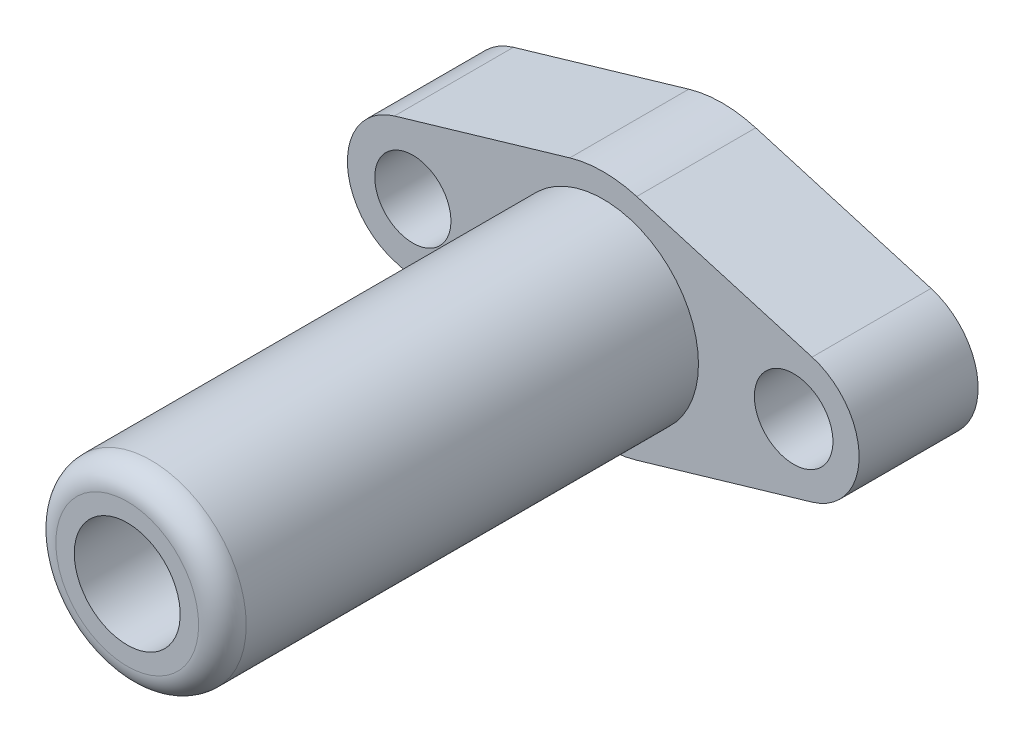
SolidWorks part; units mm, degrees
ref_plane "前视基准面" through (0, 0, 0) normal (0, 0, 1) x (1, 0, 0)
ref_plane "上视基准面" through (0, 0, 0) normal (0, 1, 0) x (1, 0, 0)
ref_plane "右视基准面" through (0, 0, 0) normal (1, 0, 0) x (0, 0, -1)
other "Configuration Table"
sketch "草图1" plane through (0, 0, 0) normal (0, 0, 1) x (1, 0, 0)
  circle A0 centre (0, 0) radius 4
  dimension "D1" = 8
extrude "凸台-拉伸1" add sketch "草图1" along normal blind 20
sketch "草图2" plane through (0, 0, 0) normal (0, 0, -1) x (-1, 0, 0)
  line L0 (-6.3901, 0) -> (7.5604, 0) construction
  line L1 (-8.7734, 2.639) -> (-1.4063, 4.7982)
  line L2 (-8.7734, -2.639) -> (-1.4063, -4.7982)
  line L3 (0, 55) -> (0, -55) construction
  line L4 (8.7734, -2.639) -> (1.4063, -4.7982)
  line L5 (8.7734, 2.639) -> (1.4063, 4.7982)
  circle A0 centre (-8, 0) radius 1.65
  circle A1 centre (8, 0) radius 1.6
  arc A2 (-1.4063, -4.7982) -> (1.4063, -4.7982) centre (0, 0) ccw
  arc A3 (-8.7734, 2.639) -> (-8.7734, -2.639) centre (-8, 0) ccw
  arc A4 (8.7734, -2.639) -> (8.7734, 2.639) centre (8, 0) ccw
  arc A5 (1.4063, 4.7982) -> (-1.4063, 4.7982) centre (0, 0) ccw
  dimension "D1" = 3.3
  dimension "D3" = 3.2
  dimension "D5" = 10
  dimension "D6" = 5.5
  dimension "D7" = 5.5
  dimension "D2" = 8
  dimension "D4" = 16
extrude "凸台-拉伸2" add sketch "草图2" along normal blind 5
sketch "草图3" plane through (0, 0, -5) normal (0, 0, -1) x (-1, 0, 0)
  circle A0 centre (0, 0) radius 2.25
  dimension "D1" = 4.5
extrude "切除-拉伸1" cut sketch "草图3" against normal blind 12
sketch "草图4" plane through (0, 0, 7) normal (0, 0, -1) x (-1, 0, 0)
  circle A0 centre (0, 0) radius 2.225
  dimension "D1" = 4.45
extrude "切除-拉伸2" cut sketch "草图4" against normal through all
fillet "圆角2" radius 1 1 edges at (4, 0, 20)
